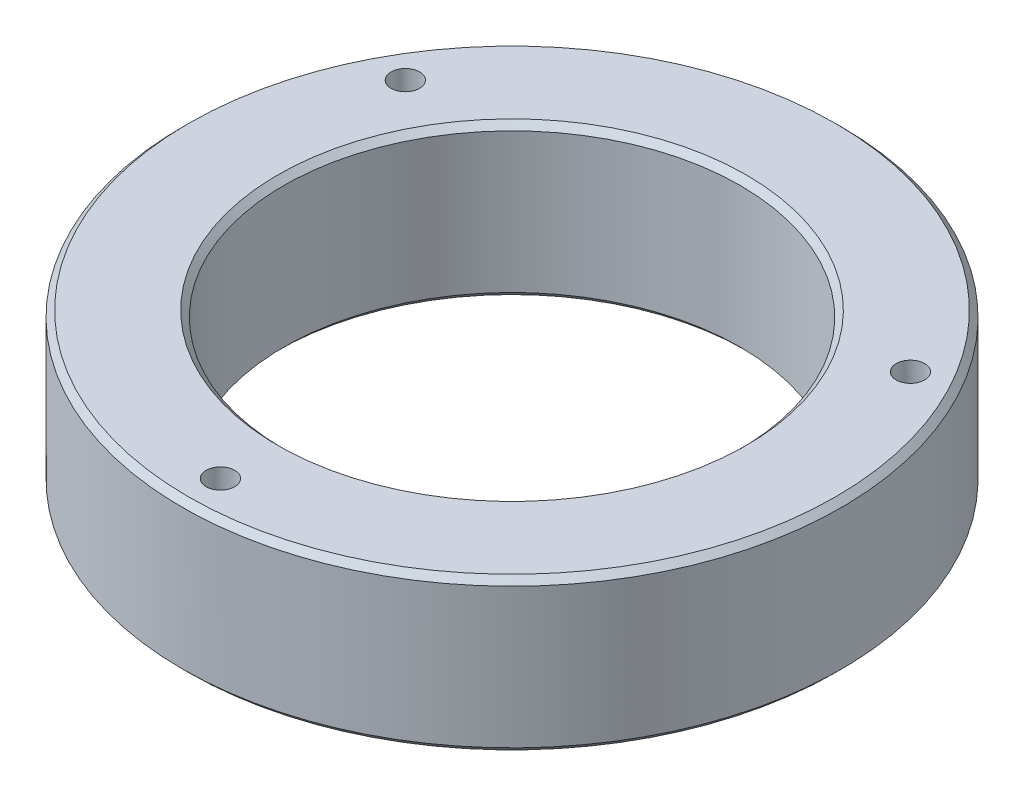
SolidWorks part; units mm, degrees
ref_plane "Front Plane" through (0, 0, 0) normal (1, 0, 0) x (0, 1, 0)
ref_plane "Top Plane" through (0, 0, 0) normal (0, 0, 1) x (0, 1, 0)
ref_plane "Right Plane" through (0, 0, 0) normal (0, 1, 0) x (-1, 0, 0)
sketch "Sketch1" plane through (0, 0, 0) normal (0, 0, 1) x (0, 1, 0)
  line L0 (-19.05, 82.5246) -> (19.05, 82.5246)
  line L1 (19.05, 82.5246) -> (19.05, 57.15)
  line L2 (19.05, 57.15) -> (-19.05, 57.15)
  line L3 (-19.05, 57.15) -> (-19.05, 82.5246)
  line L4 (-44.45, 0) -> (44.45, 0) construction
revolve "Revolve1" add sketch "Sketch1" angle 360 about L4
chamfer "Chamfer1" distance 1.524 angle 45 4 edges at (0, 19.05, -57.15) (0, -19.05, -57.15) (0, 19.05, -82.5246) (0, -19.05, -82.5246)
sketch "Sketch6" plane through (0, 0, 0) normal (0, 1, 0) x (-1, 0, 0)
  circle A0 centre (0, 73.025) radius 3.5687
  circle A1 centre (-63.246, -36.5252) radius 3.5687
  circle A2 centre (63.246, -36.5252) radius 3.5687
extrude "Cut-Extrude2" cut sketch "Sketch6" along normal blind 76.2 from offset 19.05
sketch "Sketch7" plane through (0, 0, 0) normal (0, 1, 0) x (-1, 0, 0)
  circle A0 centre (0, 73.025) radius 5.5626
  circle A1 centre (-63.246, -36.5252) radius 5.5626
  circle A2 centre (63.246, -36.5252) radius 5.5626
extrude "Cut-Extrude4" cut sketch "Sketch7" along normal blind 9.652 from offset 19.05
hole_wizard "3/8-16 Tapped Hole2" positions "Sketch11" profile "Sketch10" tap size "3/8-16" standard "ANSI Inch"
sketch "Sketch11" plane through (0, -19.05, 0) normal (0, -1, 0) x (-1, 0, 0)
  point P0 (-69.85, 0)
  point P1 (69.85, 0)
sketch "Sketch10" plane through (69.85, -19.05, 0) normal (1, 0, 0) x (0, 0, -1)
  line L0 (0, 0) -> (0, 27.7847)
  line L1 (0, 27.7847) -> (3.9687, 25.4)
  line L2 (3.9687, 25.4) -> (3.9687, 0)
  line L5 (3.9687, 0) -> (0, 0)
  line L10 (0, 27.7847) -> (-3.9687, 25.4) construction
  line L11 (0, -6.35) -> (0, 107.95) construction
  dimension "Tap Drill Dia." = 7.9375
  dimension "Tap Drill Depth" = 25.4
  dimension "Drill Angle" = 118
cosmetic thread "Hole Thread3" parameters "D1"=19.05, "D2"=9.525
cosmetic thread "Hole Thread4" parameters "D1"=19.05, "D2"=9.525
